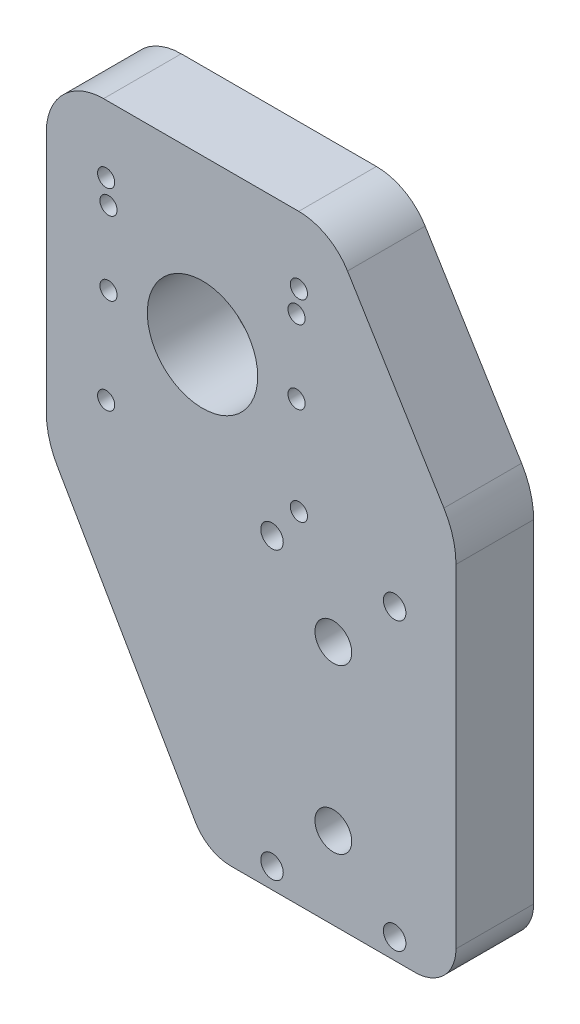
SolidWorks part; units mm, degrees
ref_plane "Front Plane" through (0, 0, 0) normal (0, 0, 1) x (1, 0, 0)
ref_plane "Top Plane" through (0, 0, 0) normal (0, 1, 0) x (1, 0, 0)
ref_plane "Right Plane" through (0, 0, 0) normal (1, 0, 0) x (0, 0, -1)
sketch "Sketch1" plane through (0, 0, 0) normal (0, 0, 1) x (1, 0, 0)
  line L0 (-130, 510) -> (13.8884, 510) construction
  line L1 (-170.2, 540.8246) -> (-129.3094, 470)
  line L2 (-116.2253, 607) -> (-90, 564.2553)
  line L15 (-90, 473) -> (-90, 564.2553)
  line L16 (-90, 473) -> (-90, 547) construction
  line L24 (-170.2, 540.8246) -> (-170.2, 607)
  line L25 (-170.2, 607) -> (-116.2253, 607)
  line L183 (-129.3094, 470) -> (-93, 470)
  arc A1 (-113.8, 602.2) -> (-116.8, 605.2) centre (-116.8, 602.2) ccw construction
  arc A13 (-90, 473) -> (-93, 470) centre (-93, 473) cw
extrude "Boss-Extrude1" add sketch "Sketch1" along normal blind 19
fillet "Fillet1" radius 10 3 edges at (-129.3094, 470, 9.5) (-170.2, 540.8246, 9.5) (-90, 564.2553, 9.5)
sketch "Sketch2" plane through (0, 0, 19) normal (0, 0, 1) x (1, 0, 0)
  circle A0 centre (-142, 577) radius 13.5
  dimension "D1" = 27
extrude "Cut-Extrude1" cut sketch "Sketch2" against normal blind 20
hole_wizard "Tap Drill for M5 Tap1" positions "Sketch5" profile "Sketch6" hole size "M5" standard "ISO" end condition through all
sketch "Sketch5" plane through (0, 0, 0) normal (0, 0, -1) x (-1, 0, 0)
  line L1 (119, 595) -> (119, 577)
  line L2 (119, 595) -> (165, 595)
  line L3 (165, 595) -> (165, 577)
  line L4 (119, 577) -> (165, 577)
  circle A1 centre (119, 595) radius 2.1
  point P2 (119, 595)
  point P4 (119, 577)
  point P6 (165, 577)
  point P8 (165, 595)
  dimension "D1" = 18
  dimension "D2" = 46
  dimension "D3" = 46
  dimension "D4" = 18
sketch "Sketch6" plane through (-119, 595, 0) normal (1, 0, 0) x (0, 1, 0)
  line L0 (0, 0) -> (0, 19)
  line L1 (0, 19) -> (2.1, 19)
  line L2 (2.1, 19) -> (2.1, 0)
  line L5 (2.1, 0) -> (0, 0)
  line L11 (0, -6.35) -> (0, 107.95) construction
  dimension "Thru Hole Dia." = 4.2
  dimension "Thru Hole Depth" = 19
hole_wizard "M5 Clearance Hole1" positions "Sketch7" profile "Sketch8" hole size "M5" standard "ISO" end condition through all
sketch "Sketch7" plane through (0, 0, 19) normal (0, 0, 1) x (1, 0, 0)
  point P0 (-95, 545)
  point P2 (-125, 545)
  point P4 (-125, 475)
  point P6 (-95, 475)
  point P8 (-110, 490)
  point P10 (-110, 530)
sketch "Sketch8" plane through (-95, 545, 19) normal (1, 0, 0) x (0, -1, 0)
  line L0 (0, 0) -> (0, 19)
  line L1 (0, 19) -> (2.75, 19)
  line L2 (2.75, 19) -> (2.75, 0)
  line L5 (2.75, 0) -> (0, 0)
  line L11 (0, -6.35) -> (0, 107.95) construction
  dimension "Thru Hole Dia." = 5.5
  dimension "Thru Hole Depth" = 19
hole_wizard "Tap Drill for M5 Tap2" positions "Sketch9" profile "Sketch10" hole size "M5" standard "ISO" end condition through all
sketch "Sketch9" plane through (0, 0, 19) normal (0, 0, 1) x (1, 0, 0)
  point P0 (-165.57, 553.43)
  point P2 (-165.57, 600.57)
  point P4 (-118.43, 553.43)
  point P6 (-118.43, 600.57)
sketch "Sketch10" plane through (-165.57, 553.43, 19) normal (1, 0, 0) x (0, -1, 0)
  line L0 (0, 0) -> (0, 19)
  line L1 (0, 19) -> (2.1, 19)
  line L2 (2.1, 19) -> (2.1, 0)
  line L5 (2.1, 0) -> (0, 0)
  line L11 (0, -6.35) -> (0, 107.95) construction
  dimension "Thru Hole Dia." = 4.2
  dimension "Thru Hole Depth" = 19
fillet "Fillet2" radius 4 2 edges at (-116.2253, 607, 9.5) (-170.2, 607, 9.5)
sketch "Sketch11" plane through (0, 0, 19) normal (0, 0, 1) x (1, 0, 0)
  line L0 (-82.9528, 571.8912) -> (-106.531, 610.3213)
  line L1 (-118.464, 617) -> (-166.2, 617)
  line L2 (-180.2, 603) -> (-180.2, 543.5041)
  line L3 (-177.5205, 533.5041) -> (-143.7432, 475)
  line L5 (-80, 480) -> (-80, 561.4321)
  line L6 (-91.4764, 566.6616) -> (-115.0546, 605.0918)
  line L7 (-118.464, 607) -> (-166.2, 607)
  line L8 (-170.2, 603) -> (-170.2, 543.5041)
  line L9 (-168.8603, 538.5041) -> (-132.1962, 475)
  line L10 (-123.5359, 470) -> (-93, 470)
  line L11 (-90, 473) -> (-90, 561.4321)
  line L12 (-91.4764, 566.6616) -> (-115.0546, 605.0918)
  line L13 (-118.464, 607) -> (-166.2, 607)
  line L14 (-170.2, 603) -> (-170.2, 543.5041)
  line L15 (-168.8603, 538.5041) -> (-132.1962, 475)
  line L16 (-135.0829, 470) -> (-90, 470)
  line L17 (-90, 473) -> (-90, 561.4321)
  line L18 (-123.5359, 470) -> (-93, 470) construction
  line L19 (-80, 473) -> (-80, 561.4321) construction
  line L20 (-123.5359, 460) -> (-93, 460) construction
  line L21 (-177.5205, 533.5041) -> (-140.8564, 470) construction
  arc A0 (-106.531, 610.3213) -> (-118.464, 617) centre (-118.464, 603) ccw
  arc A1 (-166.2, 617) -> (-180.2, 603) centre (-166.2, 603) ccw
  arc A2 (-180.2, 543.5041) -> (-177.5205, 533.5041) centre (-160.2, 543.5041) ccw
  arc A5 (-80, 561.4321) -> (-82.9528, 571.8912) centre (-100, 561.4321) ccw
  arc A6 (-115.0546, 605.0918) -> (-118.464, 607) centre (-118.464, 603) ccw
  arc A7 (-166.2, 607) -> (-170.2, 603) centre (-166.2, 603) ccw
  arc A8 (-170.2, 543.5041) -> (-168.8603, 538.5041) centre (-160.2, 543.5041) ccw
  arc A9 (-132.1962, 475) -> (-123.5359, 470) centre (-123.5359, 480) ccw
  arc A10 (-93, 470) -> (-90, 473) centre (-93, 473) ccw
  arc A11 (-90, 561.4321) -> (-91.4764, 566.6616) centre (-100, 561.4321) ccw
  arc A12 (-115.0546, 605.0918) -> (-118.464, 607) centre (-118.464, 603) ccw
  arc A13 (-166.2, 607) -> (-170.2, 603) centre (-166.2, 603) ccw
  arc A14 (-170.2, 543.5041) -> (-168.8603, 538.5041) centre (-160.2, 543.5041) ccw
  arc A15 (-132.1962, 475) -> (-123.5359, 470) centre (-123.5359, 480) ccw
  arc A16 (-93, 470) -> (-90, 473) centre (-93, 473) ccw
  arc A17 (-90, 561.4321) -> (-91.4764, 566.6616) centre (-100, 561.4321) ccw
  arc A18 (-93, 460) -> (-80, 473) centre (-93, 473) ccw construction
  arc A19 (-140.8564, 470) -> (-123.5359, 460) centre (-123.5359, 480) ccw construction
  arc A20 (-143.7432, 475) -> (-135.0829, 470) centre (-135.0829, 480) ccw
  arc A21 (-90, 470) -> (-80, 480) centre (-90, 480) ccw
  line M41 (-91.4764, 566.6616) -> (-115.0546, 605.0918)
  arc M42 (-115.0546, 605.0918) -> (-118.464, 607) centre (-118.464, 603) ccw
  line M43 (-118.464, 607) -> (-166.2, 607)
  arc M44 (-166.2, 607) -> (-170.2, 603) centre (-166.2, 603) ccw
  line M45 (-170.2, 603) -> (-170.2, 543.5041)
  arc M46 (-170.2, 543.5041) -> (-168.8603, 538.5041) centre (-160.2, 543.5041) ccw
  line M47 (-168.8603, 538.5041) -> (-132.1962, 475)
  arc M48 (-132.1962, 475) -> (-123.5359, 470) centre (-123.5359, 480) ccw
  arc M50 (-93, 470) -> (-90, 473) centre (-93, 473) ccw
  line M51 (-90, 473) -> (-90, 561.4321)
  arc M52 (-90, 561.4321) -> (-91.4764, 566.6616) centre (-100, 561.4321) ccw
  dimension "D3" = 10
  dimension "D1" = 0
  dimension "D2" = 10
extrude "Boss-Extrude2" add sketch "Sketch11" against normal up to surface (19 mm away) contours L16 A21 L5 A5 L0 A0 L1 A1 L2 A2 L3 A20 M48 M47 M46 M45 M44 M43 M42 M41 M52 M51 M50 up to face at (-122.25, 475, 0)
hole_wizard "M8 Clearance Hole1" positions "3DSketch1" profile "Sketch12" hole size "M8" standard "ISO" end condition through all
sketch3d "3DSketch1"
  line L0 (-110, 490, 0) -> (-110, 490, 19) construction
  line L1 (-110, 530, 0) -> (-110, 530, 19) construction
  point P0 (-110, 490, 0)
  point P4 (-110, 530, 0)
sketch "Sketch12" plane through (-110, 490, 0) normal (1, 0, 0) x (0, 1, 0)
  line L0 (0, 0) -> (0, 19)
  line L1 (0, 19) -> (4.5, 19)
  line L2 (4.5, 19) -> (4.5, 0)
  line L5 (4.5, 0) -> (0, 0)
  line L11 (0, -6.35) -> (0, 107.95) construction
  dimension "Thru Hole Dia." = 9
  dimension "Thru Hole Depth" = 19
